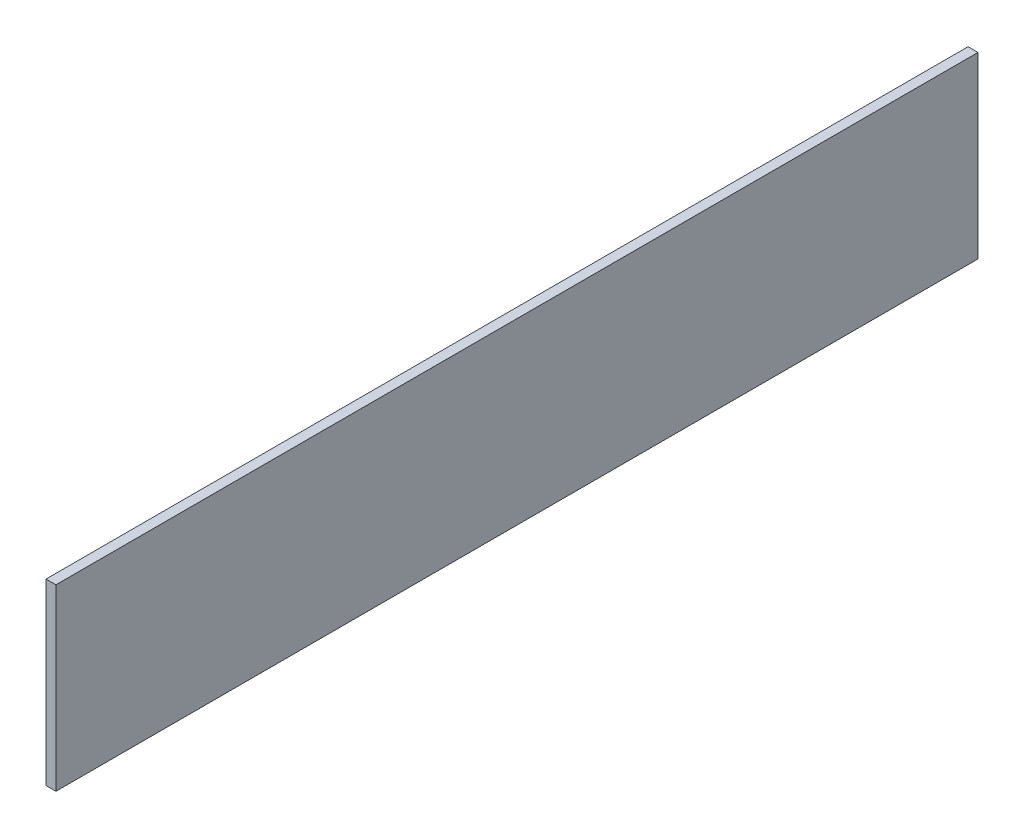
SolidWorks part; units mm, degrees
ref_plane "Front Plane" through (0, 0, 0) normal (0, 0, 1) x (1, 0, 0)
ref_plane "Top Plane" through (0, 0, 0) normal (0, 1, 0) x (1, 0, 0)
ref_plane "Right Plane" through (0, 0, 0) normal (1, 0, 0) x (0, 0, -1)
sketch "Sketch1" plane through (0, 0, 0) normal (0, 0, 1) x (1, 0, 0)
  line L1 (0, 0) -> (3.175, 0)
  line L2 (0, 0) -> (0, 57.15)
  line L3 (0, 57.15) -> (3.175, 57.15)
  line L4 (3.175, 0) -> (3.175, 57.15)
  dimension "D1" = 3.175
  dimension "D2" = 57.15
extrude "Boss-Extrude1" add sketch "Sketch1" along normal blind 294.64
